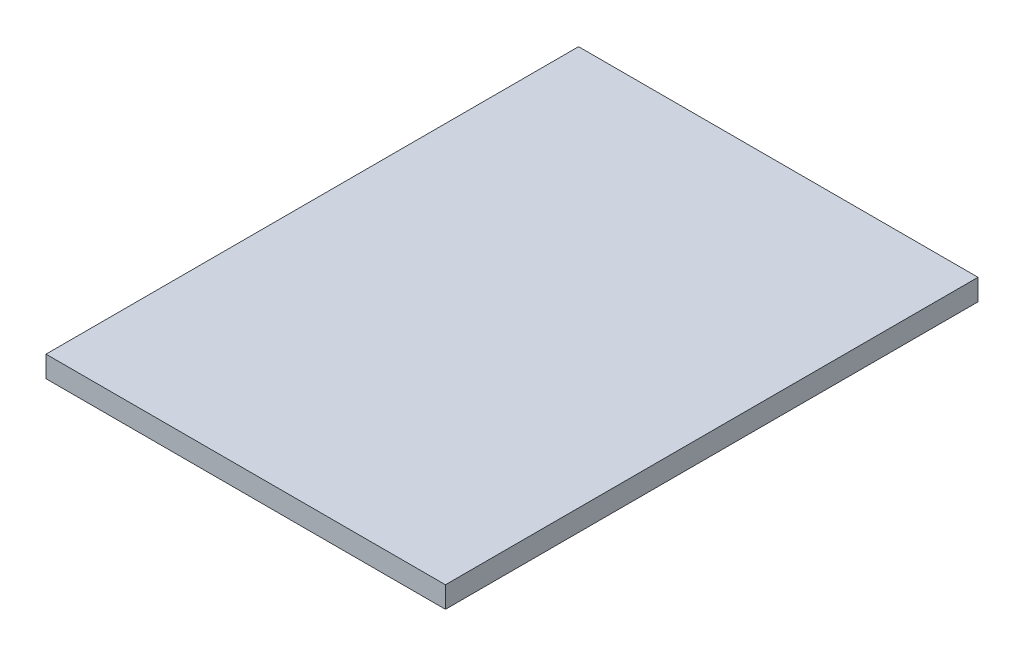
SolidWorks part; units mm, degrees
material "Сосна"
ref_plane "Спереди" through (0, 0, 0) normal (0, 0, 1) x (1, 0, 0)
ref_plane "Сверху" through (0, 0, 0) normal (0, 1, 0) x (1, 0, 0)
ref_plane "Справа" through (0, 0, 0) normal (1, 0, 0) x (0, 0, -1)
sketch3d "Трехмерный эскиз1"
  line L22 (105.6358, 10, 21.815) -> (180.6358, 10, 21.815)
  line L23 (105.6358, 10, 21.815) -> (105.6358, 10, 121.815)
  line L24 (105.6358, 10, 121.815) -> (180.6358, 10, 121.815)
  line L25 (180.6358, 10, 21.815) -> (180.6358, 10, 121.815)
  dimension "D16" = 75
  dimension "D17" = 100
extrude "Бобышка-Вытянуть2" add sketch "Трехмерный эскиз1" along direction (0, 1, 0) on the side of the normal blind 4
